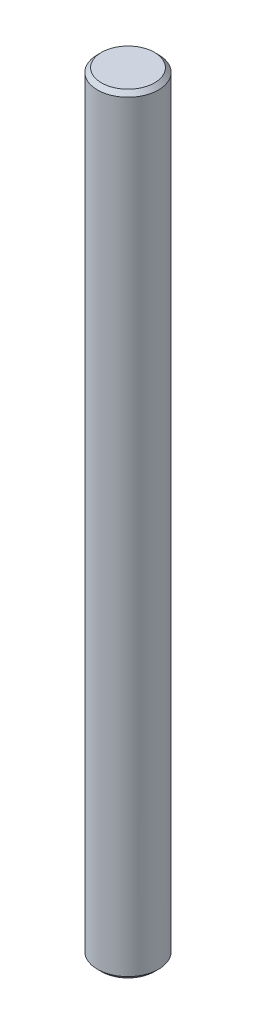
SolidWorks part; units mm, degrees
ref_plane "Front Plane" through (0, 0, 0) normal (0, 0, 1) x (1, 0, 0)
ref_plane "Top Plane" through (0, 0, 0) normal (0, 1, 0) x (1, 0, 0)
ref_plane "Right Plane" through (0, 0, 0) normal (1, 0, 0) x (0, 0, -1)
sketch "Sketch1" plane through (0, 0, 0) normal (0, 0, 1) x (1, 0, 0)
  line L5 (7.5, 189) -> (0, 189)
  line L6 (7.5, 189) -> (7.5, 0)
  line L7 (7.5, 0) -> (0, 0)
  line L8 (0, 189) -> (0, 0)
  line L9 (7.5, 189) -> (0, 0) construction
  line L10 (7.5, 0) -> (0, 189) construction
  point P0 (3.75, 94.5)
  dimension "D1" = 7.5
  dimension "D2" = 189
revolve "Revolve1" add sketch "Sketch1" angle 360 about L8
ref_plane "Plane1" through (0, 169, 0) normal (0, 1, 0) x (1, 0, 0)
sketch "Sketch2" plane through (0, 169, 0) normal (0, 1, 0) x (1, 0, 0)
  line L1 (1.5, 9) -> (-1.5, 9)
  line L2 (1.5, 9) -> (1.5, 6)
  line L3 (1.5, 6) -> (-1.5, 6)
  line L4 (-1.5, 9) -> (-1.5, 6)
  line L5 (1.5, 9) -> (-1.5, 6) construction
  line L6 (1.5, 6) -> (-1.5, 9) construction
  circle A0 centre (0, 0) radius 7.5 construction
  point P0 (0, 7.5)
  dimension "D1" = 3
extrude "Cut-Extrude1" cut sketch "Sketch2" against normal blind 18
ref_plane "Plane2" through (0, 104, 0) normal (0, -1, 0) x (-1, 0, 0)
sketch "Sketch3" plane through (0, 104, 0) normal (0, -1, 0) x (-1, 0, 0)
  line L1 (-1.5, 9) -> (1.5, 9)
  line L2 (-1.5, 9) -> (-1.5, 6)
  line L3 (-1.5, 6) -> (1.5, 6)
  line L4 (1.5, 9) -> (1.5, 6)
  line L5 (-1.5, 9) -> (1.5, 6) construction
  line L6 (-1.5, 6) -> (1.5, 9) construction
  circle A0 centre (0, 0) radius 7.5 construction
  point P0 (0, 7.5)
  dimension "D1" = 3
extrude "Cut-Extrude2" cut sketch "Sketch3" along normal blind 15
chamfer "Chamfer1" distance 1 angle 45 2 edges at (-7.5, 0, 0) (-7.5, 189, 0)
